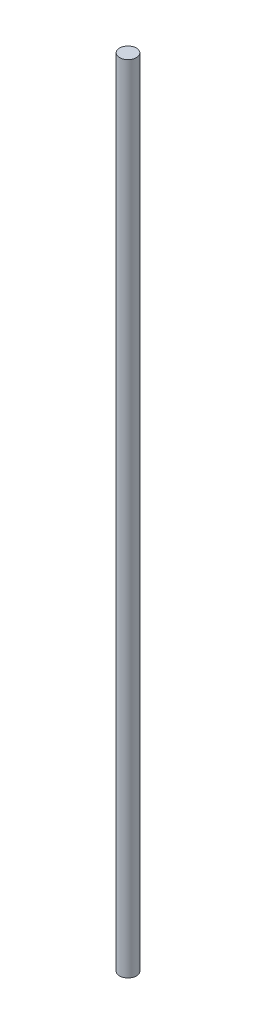
SolidWorks part; units mm, degrees
material "Polylactide (PLA)"
ref_plane "Front Plane" through (0, 0, 0) normal (0, 0, 1) x (1, 0, 0)
ref_plane "Top Plane" through (0, 0, 0) normal (0, 1, 0) x (1, 0, 0)
ref_plane "Right Plane" through (0, 0, 0) normal (1, 0, 0) x (0, 0, -1)
sketch "Sketch1" plane through (0, 0, 0) normal (0, 1, 0) x (1, 0, 0)
  circle A0 centre (0, 0) radius 3
  dimension "D1" = 6
extrude "Boss-Extrude1" add sketch "Sketch1" along normal blind 285
